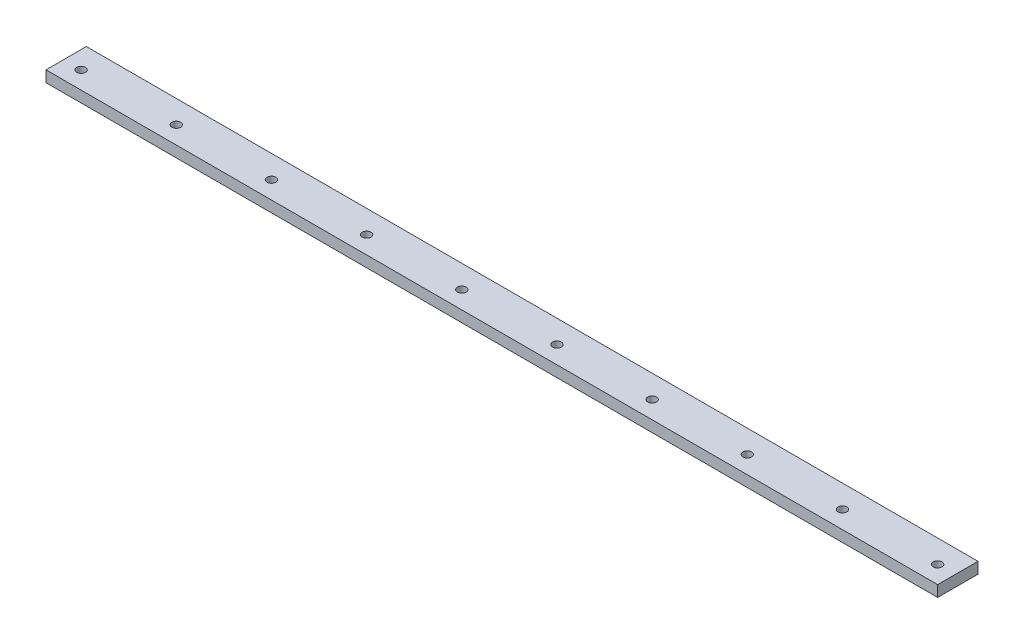
SolidWorks part; units mm, degrees
ref_plane "Front Plane" through (0, 0, 0) normal (0, 0, 1) x (1, 0, 0)
ref_plane "Top Plane" through (0, 0, 0) normal (0, 1, 0) x (1, 0, 0)
ref_plane "Right Plane" through (0, 0, 0) normal (1, 0, 0) x (0, 0, -1)
sketch "Sketch1" plane through (0, 0, 0) normal (0, 1, 0) x (1, 0, 0)
  line L0 (-254, 10) -> (254, 10) construction
  line L5 (-254, -10) -> (254, -10)
  line L6 (-254, -10) -> (-254, 13)
  line L7 (-254, 13) -> (254, 13)
  line L8 (254, -10) -> (254, 13)
  line L9 (0, 10) -> (0, -10) construction
  line L10 (-244, -10) -> (-244, 0) construction
  line L11 (-244, 0) -> (-254, 0) construction
  line L12 (244, 0) -> (254, 0) construction
  circle A0 centre (-244, 0) radius 2.5
  circle A1 centre (-189.7778, 0) radius 2.5
  circle A2 centre (-135.5556, 0) radius 2.5
  circle A3 centre (-81.3333, 0) radius 2.5
  circle A4 centre (-27.1111, 0) radius 2.5
  circle A5 centre (27.1111, 0) radius 2.5
  circle A6 centre (81.3333, 0) radius 2.5
  circle A7 centre (135.5556, 0) radius 2.5
  circle A8 centre (189.7778, 0) radius 2.5
  circle A9 centre (244, 0) radius 2.5
  point P4 (0, 13)
  dimension "D1" = 5
  dimension "D2" = 20
  dimension "D3" = 508
  dimension "D4" = 3
extrude "Boss-Extrude1" add sketch "Sketch1" along normal mid plane 6.35
